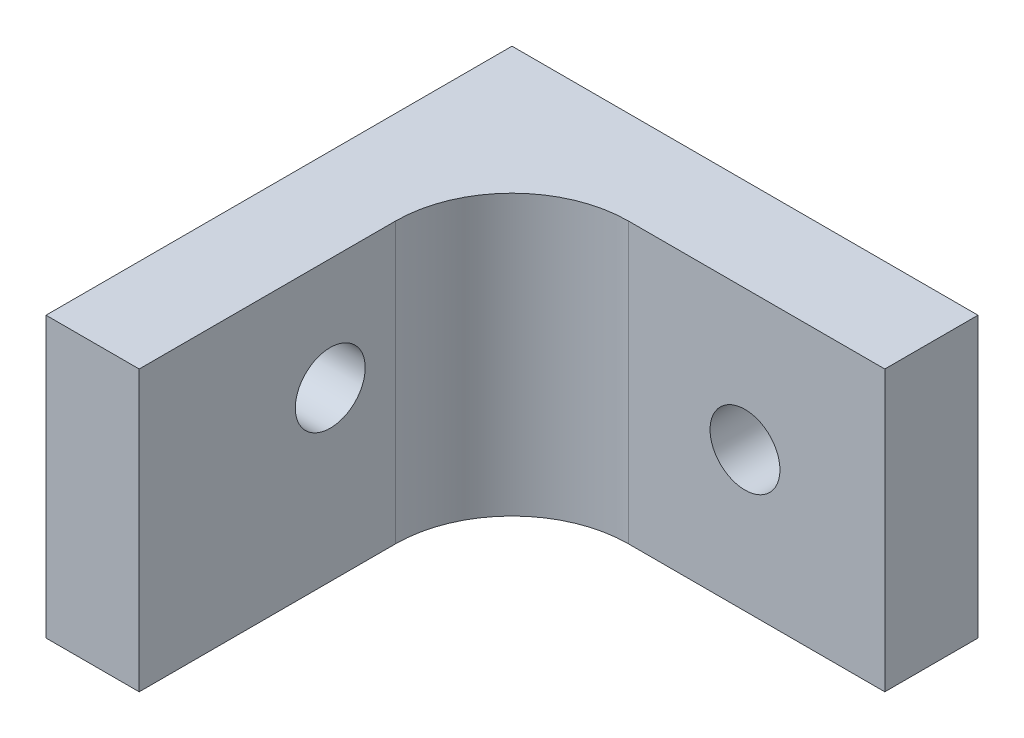
SolidWorks part; units mm, degrees
ref_plane "Front Plane" through (0, 0, 0) normal (0, 0, 1) x (1, 0, 0)
ref_plane "Top Plane" through (0, 0, 0) normal (0, 1, 0) x (1, 0, 0)
ref_plane "Right Plane" through (0, 0, 0) normal (1, 0, 0) x (0, 0, -1)
sketch "Sketch1" plane through (0, 0, 0) normal (0, 0, 1) x (1, 0, 0)
  line L0 (-3, -6) -> (-3, -3) construction
  line L1 (0, -6) -> (-10, -6)
  line L2 (0, -6) -> (0, 0)
  line L3 (0, 0) -> (-10, 0)
  line L4 (-10, -6) -> (-10, 0)
  line L5 (-3, -3) -> (0, -3) construction
  circle A0 centre (-3, -3) radius 0.75
  dimension "D5" = 1.5
  dimension "D1" = 10
  dimension "D2" = 6
  dimension "D3" = 3
  dimension "D4" = 3
extrude "Boss-Extrude1" add sketch "Sketch1" along normal blind 2
sketch "Sketch2" plane through (-10, 0, 0) normal (-1, 0, 0) x (0, 0, 1)
  line L0 (5.9, 0) -> (5.9, -2.4) construction
  line L1 (0, 0) -> (10, 0)
  line L2 (0, 0) -> (0, -6)
  line L3 (0, -6) -> (10, -6)
  line L4 (10, 0) -> (10, -6)
  line L5 (5.9, -2.4) -> (10, -2.4) construction
  circle A2 centre (5.9, -2.4) radius 0.75
  dimension "D5" = 1.5
  dimension "D1" = 6
  dimension "D2" = 10
  dimension "D3" = 2.4
  dimension "D4" = 4.1
extrude "Boss-Extrude2" add sketch "Sketch2" against normal blind 2
fillet "Fillet2" radius 2.5 1 edges at (-8, -3, 2)
